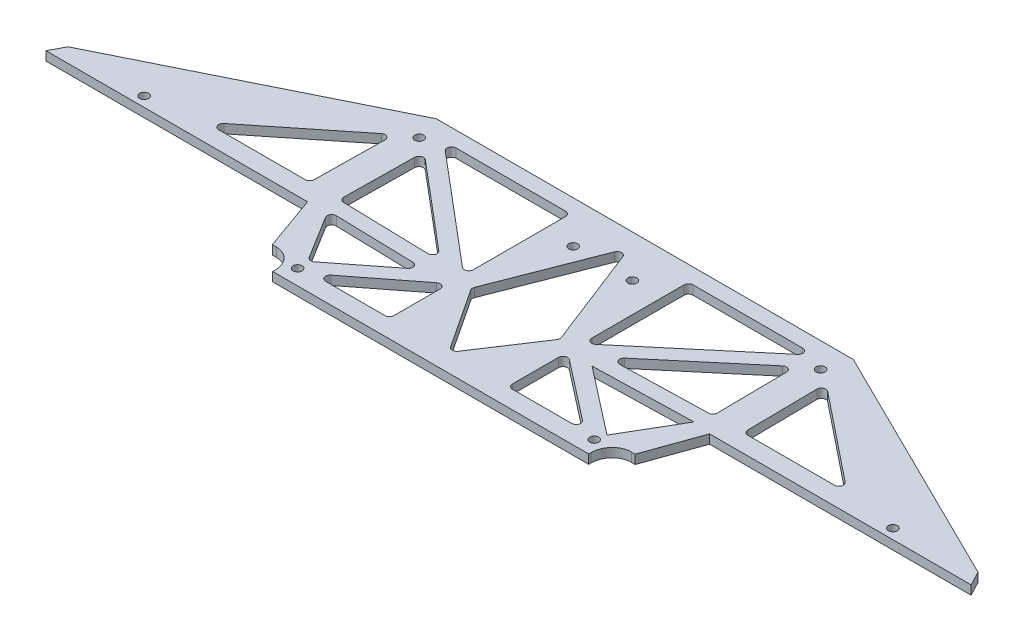
SolidWorks part; units mm, degrees
material "Титан Ti-8Mn, отожженный"
ref_plane "Спереди" through (0, 0, 0) normal (0, 0, 1) x (1, 0, 0)
ref_plane "Сверху" through (0, 0, 0) normal (0, 1, 0) x (1, 0, 0)
ref_plane "Справа" through (0, 0, 0) normal (1, 0, 0) x (0, 0, -1)
sketch "Эскиз1" plane through (0, 0, 0) normal (0, 1, 0) x (1, 0, 0)
  line L0 (-214.3273, -7.5266) -> (-144.9454, -7.5266)
  line L1 (-144.9454, -7.5266) -> (-144.2329, 48.5485)
  line L2 (-144.2329, 48.5485) -> (-214.3273, -7.5266)
  line L17 (-124.2345, 48.2944) -> (-124.947, -7.7807)
  line L18 (-124.947, -7.7807) -> (-55.5874, -9.5435)
  line L19 (-55.5874, -9.5435) -> (-124.2345, 48.2944)
  line L20 (-39.5847, 61.2321) -> (-124.0701, 61.2321)
  line L21 (-124.0701, 61.2321) -> (-39.5847, -9.9502)
  line L22 (-39.5847, -9.9502) -> (-39.5847, 61.2321)
  line L23 (-29.5847, -14.7554) -> (0, -59.5689)
  line L24 (0, -59.5689) -> (29.5847, -14.7554)
  line L25 (29.5847, -14.7554) -> (0, 61.2321)
  line L26 (0, 61.2321) -> (-29.5847, -14.7554)
  line L27 (-90.9973, -59.5689) -> (-39.5847, -59.5689)
  line L28 (-39.5847, -59.5689) -> (-39.5847, -19.5606)
  line L29 (-39.5847, -19.5606) -> (-90.9973, -59.5689)
  line L30 (-99.8531, -54.0319) -> (-55.8415, -19.5402)
  line L31 (-55.8415, -19.5402) -> (-122.2205, -17.8532)
  line L32 (-122.2205, -17.8532) -> (-99.8531, -54.0319)
  line L33 (124.0701, 61.2321) -> (39.5847, 61.2321)
  line L34 (39.5847, 61.2321) -> (39.5847, -9.9502)
  line L35 (39.5847, -9.9502) -> (124.0701, 61.2321)
  line L36 (124.947, -7.7807) -> (124.2345, 48.2944)
  line L37 (124.2345, 48.2944) -> (55.5874, -9.5435)
  line L38 (55.5874, -9.5435) -> (124.947, -7.7807)
  line L39 (100.7854, -54.5222) -> (122.2205, -17.8532)
  line L40 (122.2205, -17.8532) -> (55.8415, -19.5402)
  line L41 (55.8415, -19.5402) -> (100.7854, -54.5222)
  line L42 (90.9973, -59.5689) -> (39.5847, -19.5606)
  line L43 (39.5847, -19.5606) -> (39.5847, -59.5689)
  line L44 (39.5847, -59.5689) -> (90.9973, -59.5689)
  line L45 (144.9454, -7.5266) -> (214.3273, -7.5266)
  line L46 (214.3273, -7.5266) -> (144.2329, 48.5485)
  line L47 (144.2329, 48.5485) -> (144.9454, -7.5266)
  line L90 (309.1778, -19.5266) -> (304.1209, -9.8693)
  line L91 (304.1209, -9.8693) -> (139.3391, 71.5689)
  line L92 (139.3391, 71.5689) -> (-139.3391, 71.5689)
  line L93 (-139.3391, 71.5689) -> (-304.1209, -9.8693)
  line L94 (-304.1209, -9.8693) -> (-309.1778, -19.5266)
  line L95 (-309.1778, -19.5266) -> (-134.3675, -19.5266)
  line L96 (-134.3675, -19.5266) -> (-121.2555, -56.1379)
  line L97 (-121.2555, -56.1379) -> (-118.625, -56.1379)
  line L98 (-105.625, -70.0345) -> (-105.625, -71.5689)
  line L99 (-105.625, -71.5689) -> (105.625, -71.5689)
  line L100 (105.625, -71.5689) -> (105.625, -70.0345)
  line L101 (118.625, -56.1379) -> (121.2555, -56.1379)
  line L102 (121.2555, -56.1379) -> (134.3675, -19.5266)
  line L103 (134.3675, -19.5266) -> (309.1778, -19.5266)
  spline S6 degree 3 poles (-118.625, -56.1379) (-117.736, -56.1379) (-116.8636, -56.2337) (-115.5785, -56.5144) (-115.154, -56.631) (-114.3133, -56.9114) (-113.9003, -57.0743) (-112.7003, -57.6218) (-111.9448, -58.0669) (-110.877, -58.8532) (-110.5324, -59.1355) (-109.8797, -59.7269) (-109.2597, -60.3482) (-108.7027, -61.0273) (-108.1772, -61.7352) (-107.9292, -62.1053) (-107.245, -63.2392) (-106.8649, -64.0295) (-106.2494, -65.6753) (-106.0139, -66.537) (-105.7033, -68.2702) (-105.625, -69.1471) (-105.625, -70.0345) knots 0 0 0 0 0.125 0.125 0.1875 0.1875 0.25 0.25 0.375 0.375 0.4375 0.4375 0.5 0.5625 0.5625 0.625 0.625 0.75 0.75 0.875 0.875 1 1 1 1
  spline S7 degree 3 poles (105.625, -70.0345) (105.625, -69.1462) (105.7034, -68.271) (105.9348, -66.9775) (106.031, -66.5495) (106.2626, -65.7001) (106.3988, -65.2767) (106.8631, -64.0325) (107.2437, -63.2428) (107.9213, -62.1177) (108.165, -61.7527) (108.6899, -61.0435) (108.9725, -60.6978) (109.8603, -59.7155) (110.5082, -59.1269) (111.5659, -58.3449) (111.9329, -58.1012) (112.6971, -57.6496) (113.0906, -57.4441) (114.29, -56.8957) (115.1204, -56.6163) (116.4138, -56.331) (116.8545, -56.2584) (117.7368, -56.1621) (118.1799, -56.1379) (118.625, -56.1379) knots 0 0 0 0 0.125 0.125 0.1875 0.1875 0.25 0.25 0.375 0.375 0.4375 0.4375 0.5 0.5 0.625 0.625 0.6875 0.6875 0.75 0.75 0.875 0.875 0.9375 0.9375 1 1 1 1
extrude "Бобышка-Вытянуть1" add sketch "Эскиз1" along normal blind 6
sketch "Эскиз2" plane through (0, 6, 0) normal (0, 1, 0) x (1, 0, 0)
  line L0 (-244.923, -18.3722) -> (-255.5834, -7.3716) construction
  line L4 (-124.0701, 61.2321) -> (-144.2329, 48.5485) construction
  line L8 (-107.2803, -59.5689) -> (-90.9973, -59.5689) construction
  line L11 (-99.1388, -53.2334) -> (-99.1388, -69.5689) construction
  line L13 (-97.0596, -51.6153) -> (-104.9078, -57.7227) construction
  line L14 (-39.5847, 25.6409) -> (0, 61.2321) construction
  line L18 (0, 61.2321) -> (0, -136.1487) construction
  line L19 (39.5847, 25.6409) -> (0, 61.2321) construction
  line L20 (97.0596, -51.6153) -> (104.9078, -57.7227) construction
  line L21 (99.1388, -53.2334) -> (99.1388, -69.5689) construction
  line L22 (107.2803, -59.5689) -> (90.9973, -59.5689) construction
  line L23 (124.0701, 61.2321) -> (144.2329, 48.5485) construction
  line L25 (244.923, -18.3722) -> (255.5834, -7.3716) construction
  circle A2 centre (-250.2532, -12.8719) radius 3
  circle A3 centre (-134.1515, 54.8903) radius 3
  circle A6 centre (-99.1388, -61.4011) radius 3
  circle A7 centre (-19.7924, 43.4365) radius 3
  circle A8 centre (19.7924, 43.4365) radius 3
  circle A9 centre (99.1388, -61.4011) radius 3
  circle A10 centre (134.1515, 54.8903) radius 3
  circle A11 centre (250.2532, -12.8719) radius 3
extrude "Вырез-Вытянуть1" cut sketch "Эскиз2" against normal through all
fillet "Скругление1" radius 3 31 edges at (39.5847, 3, 9.9502) (39.5847, 3, -61.2321) (124.0701, 3, -61.2321) (124.2345, 3, -48.2944) (144.2329, 3, -48.5485) (214.3273, 3, 7.5266) (144.9454, 3, 7.5266) (124.947, 3, 7.7807) (55.5874, 3, 9.5435) (39.5847, 3, 59.5689) (39.5847, 3, 19.5606) (90.9973, 3, 59.5689) (0, 3, 59.5689) (-29.5847, 3, 14.7554) (0, 3, -61.2321) (29.5847, 3, 14.7554) (-55.8415, 3, 19.5402) (-39.5847, 3, 19.5606) (-90.9973, 3, 59.5689) (-124.0701, 3, -61.2321) (-39.5847, 3, 59.5689) (-39.5847, 3, 9.9502) (-39.5847, 3, -61.2321) (-214.3273, 3, 7.5266) (-144.9454, 3, 7.5266) (-99.8531, 3, 54.0319) (-122.2205, 3, 17.8532) (-124.947, 3, 7.7807) (-55.5874, 3, 9.5435) (-144.2329, 3, -48.5485) (-124.2345, 3, -48.2944)
